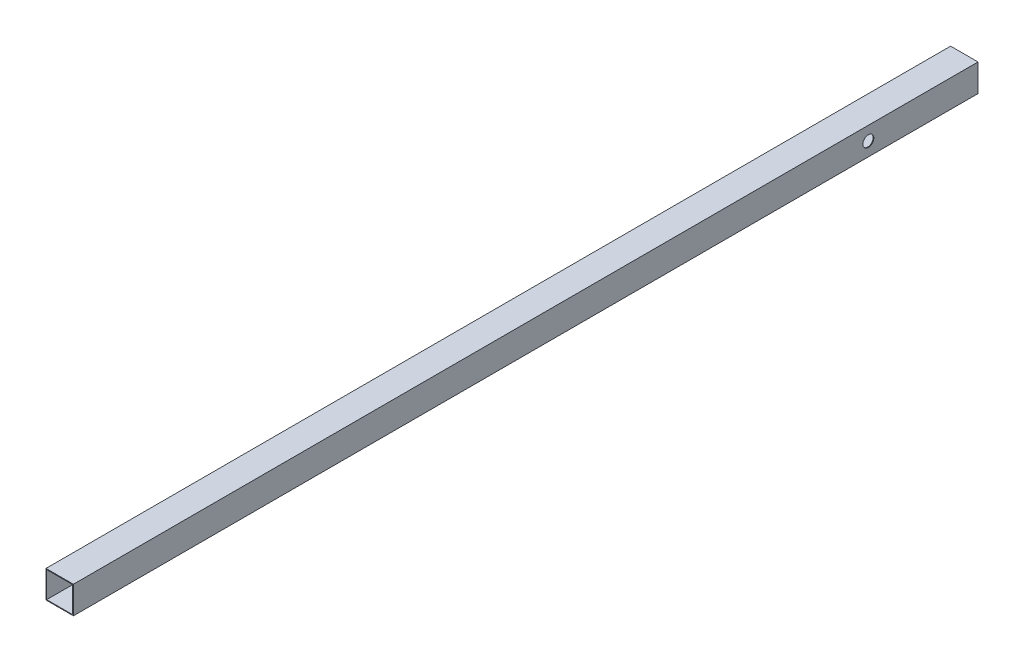
SolidWorks part; units mm, degrees
ref_plane "Front Plane" through (0, 0, 0) normal (0, 0, 1) x (1, 0, 0)
ref_plane "Top Plane" through (0, 0, 0) normal (0, 1, 0) x (1, 0, 0)
ref_plane "Right Plane" through (0, 0, 0) normal (1, 0, 0) x (0, 0, -1)
sketch "Sketch1" plane through (0, 0, 0) normal (0, 0, 1) x (1, 0, 0)
  line L1 (-10, 10) -> (10, 10)
  line L2 (-10, 10) -> (-10, -10)
  line L3 (-10, -10) -> (10, -10)
  line L4 (10, 10) -> (10, -10)
  line L5 (-10, 10) -> (10, -10) construction
  line L6 (-10, -10) -> (10, 10) construction
  point P0 (0, 0)
  dimension "D1" = 20
  dimension "D2" = 20
extrude "Boss-Extrude1" add sketch "Sketch1" along normal blind 660
sketch "Sketch2" plane through (0, 0, 0) normal (0, 0, -1) x (-1, 0, 0)
  line L1 (-9.5, 9.5) -> (9.5, 9.5)
  line L2 (-9.5, 9.5) -> (-9.5, -9.5)
  line L3 (-9.5, -9.5) -> (9.5, -9.5)
  line L4 (9.5, 9.5) -> (9.5, -9.5)
  line L5 (-9.5, 9.5) -> (9.5, -9.5) construction
  line L6 (-9.5, -9.5) -> (9.5, 9.5) construction
  point P0 (0, 0)
  dimension "D1" = 19
extrude "Cut-Extrude1" cut sketch "Sketch2" against normal blind 660
sketch "Sketch3" plane through (10, 0, 0) normal (1, 0, 0) x (0, 0, -1)
  line L0 (-660, 0) -> (0, 0) construction
  line L1 (-660, -10) -> (-660, 10) construction
  line L2 (0, -10) -> (0, 10) construction
  circle A0 centre (-80, 0) radius 4
  dimension "D1" = 8
  dimension "D2" = 80
extrude "Cut-Extrude2" cut sketch "Sketch3" against normal blind 20
